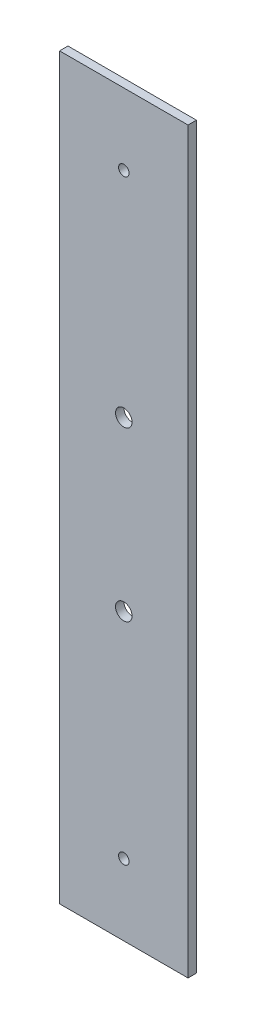
SolidWorks part; units mm, degrees
ref_plane "Front Plane" through (0, 0, 0) normal (0, 0, 1) x (1, 0, 0)
ref_plane "Top Plane" through (0, 0, 0) normal (0, 1, 0) x (1, 0, 0)
ref_plane "Right Plane" through (0, 0, 0) normal (1, 0, 0) x (0, 0, -1)
sketch "Sketch1" plane through (0, 0, 0) normal (0, 0, 1) x (1, 0, 0)
  line L1 (19.431, -114.3) -> (-19.431, -114.3)
  line L2 (19.431, -114.3) -> (19.431, 114.3)
  line L3 (19.431, 114.3) -> (-19.431, 114.3)
  line L4 (-19.431, -114.3) -> (-19.431, 114.3)
  line L5 (19.431, -114.3) -> (-19.431, 114.3) construction
  line L6 (19.431, 114.3) -> (-19.431, -114.3) construction
  point P0 (0, 0)
  dimension "D1" = 38.862
  dimension "D2" = 228.6
extrude "Boss-Extrude1" add sketch "Sketch1" along normal blind 2.54
sketch "Sketch2" plane through (0, 0, 2.54) normal (0, 0, 1) x (1, 0, 0)
  line L0 (-19.431, -114.3) -> (19.431, -114.3) construction
  line L1 (0, -90.17) -> (0, -114.3) construction
  circle A0 centre (0, -90.17) radius 1.5875
  dimension "D2" = 3.175
  dimension "D1" = 24.13
extrude "Cut-Extrude1" cut sketch "Sketch2" against normal through all
mirror "Mirror1" about plane through (0, 0, 0) normal (0, 1, 0) of "Cut-Extrude1"
sketch "Sketch3" plane through (0, 0, 2.54) normal (0, 0, 1) x (1, 0, 0)
  line L0 (0, 88.5825) -> (0, -90.17) construction
  line L1 (0, 0) -> (2.5, 0) construction
  line L2 (2.5, 0) -> (2.5, 25.4) construction
  line L3 (2.5, 0) -> (2.5, -25.4) construction
  circle A0 centre (0, 90.17) radius 1.5875 construction
  circle A1 centre (0, -25.4) radius 2.5
  circle A2 centre (0, 25.4) radius 2.5
  dimension "D2" = 5
  dimension "D1" = 25.4
extrude "Cut-Extrude2" cut sketch "Sketch3" against normal blind 5.08
sketch "Sketch4" plane through (0, 0, 2.54) normal (0, 0, 1) x (1, 0, 0)
  line L0 (19.431, -114.3) -> (19.431, 114.3) construction
  line L1 (-19.431, 114.3) -> (19.431, 114.3)
  line L2 (-19.431, 114.3) -> (-19.431, 111.76)
  line L3 (-19.431, 111.76) -> (19.431, 111.76)
  line L4 (19.431, 114.3) -> (19.431, 111.76)
  line L5 (-19.431, 114.3) -> (-19.431, -114.3) construction
  line L6 (19.431, -114.3) -> (-19.431, -114.3)
  line L7 (19.431, -114.3) -> (19.431, -111.76)
  line L8 (19.431, -111.76) -> (-19.431, -111.76)
  line L9 (-19.431, -114.3) -> (-19.431, -111.76)
  dimension "D1" = 2.54
extrude "Cut-Extrude3" cut sketch "Sketch4" against normal through all
